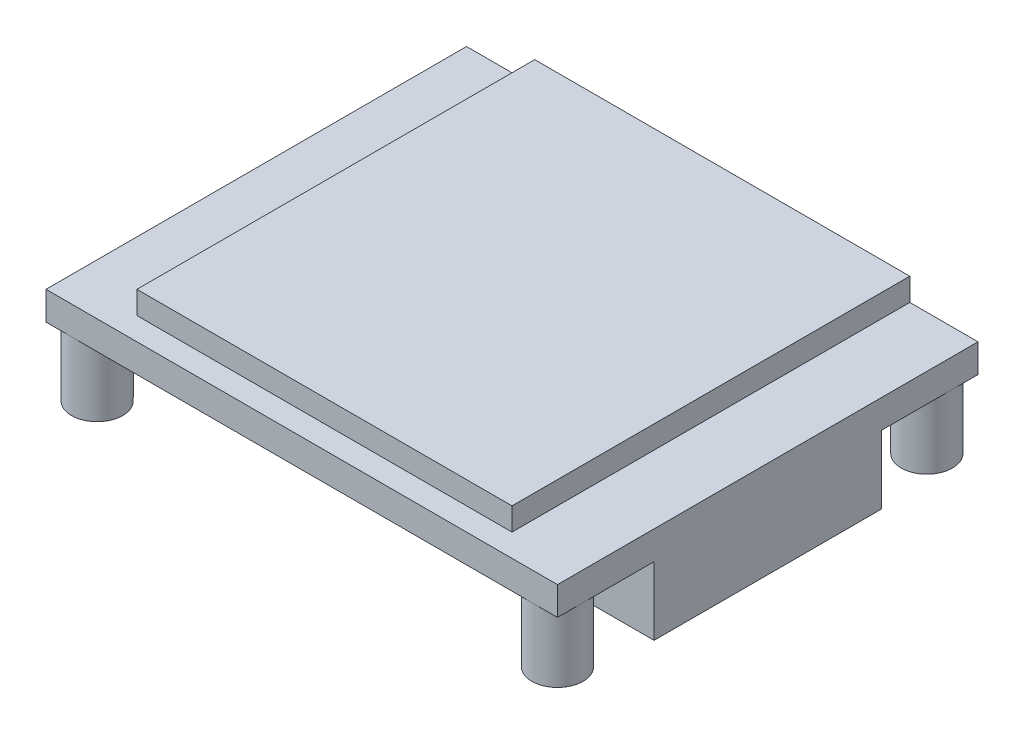
SolidWorks part; units mm, degrees
ref_plane "前视基准面" through (0, 0, 0) normal (0, 0, 1) x (1, 0, 0)
ref_plane "上视基准面" through (0, 0, 0) normal (0, 1, 0) x (1, 0, 0)
ref_plane "右视基准面" through (0, 0, 0) normal (1, 0, 0) x (0, 0, -1)
sketch "草图1" plane through (0, 0, 0) normal (0, 1, 0) x (1, 0, 0)
  line L1 (0, 0) -> (45, 0)
  line L2 (0, 0) -> (0, 37)
  line L3 (0, 37) -> (45, 37)
  line L4 (45, 0) -> (45, 37)
  dimension "D1" = 45
  dimension "D2" = 37
extrude "凸台-拉伸1" add sketch "草图1" along normal blind 2.5
sketch "草图2" plane through (0, 2.5, 0) normal (0, 1, 0) x (1, 0, 0)
  line L0 (45, 37) -> (0, 37) construction
  line L1 (6, 37) -> (39, 37)
  line L2 (6, 37) -> (6, 2)
  line L3 (6, 2) -> (39, 2)
  line L4 (39, 37) -> (39, 2)
  point P6 (22.5, 37)
  point P7 (22.5, 37)
  point P8 (0, 0)
  dimension "D1" = 33
  dimension "D2" = 35
extrude "凸台-拉伸2" add sketch "草图2" along normal blind 2
sketch "草图3" plane through (0, 0, 0) normal (0, -1, 0) x (1, 0, 0)
  line L0 (45, 0) -> (45, -37) construction
  line L1 (45, -28.5) -> (38, -28.5)
  line L2 (45, -28.5) -> (45, -8.5)
  line L3 (45, -8.5) -> (38, -8.5)
  line L4 (38, -28.5) -> (38, -8.5)
  line L5 (45, -37) -> (0, -37) construction
  line L6 (22.5, -37) -> (22.5, 0) construction
  line L7 (0, 0) -> (45, 0) construction
  line L8 (0, -18.5) -> (45, -18.5) construction
  line L9 (0, -37) -> (0, 0) construction
  circle A0 centre (42.75, -34.75) radius 1.5
  circle A1 centre (42.75, -34.75) radius 2.25
  circle A2 centre (42.75, -2.25) radius 2.25
  circle A3 centre (42.75, -2.25) radius 1.5
  circle A4 centre (2.25, -2.25) radius 1.5
  circle A5 centre (2.25, -2.25) radius 2.25
  circle A6 centre (2.25, -34.75) radius 2.25
  circle A7 centre (2.25, -34.75) radius 1.5
  point P9 (45, -18.5)
  point P12 (45, -18.5)
  dimension "D1" = 3
  dimension "D2" = 4.5
  dimension "D3" = 20
  dimension "D4" = 7
extrude "凸台-拉伸3" add sketch "草图3" along normal blind 6
